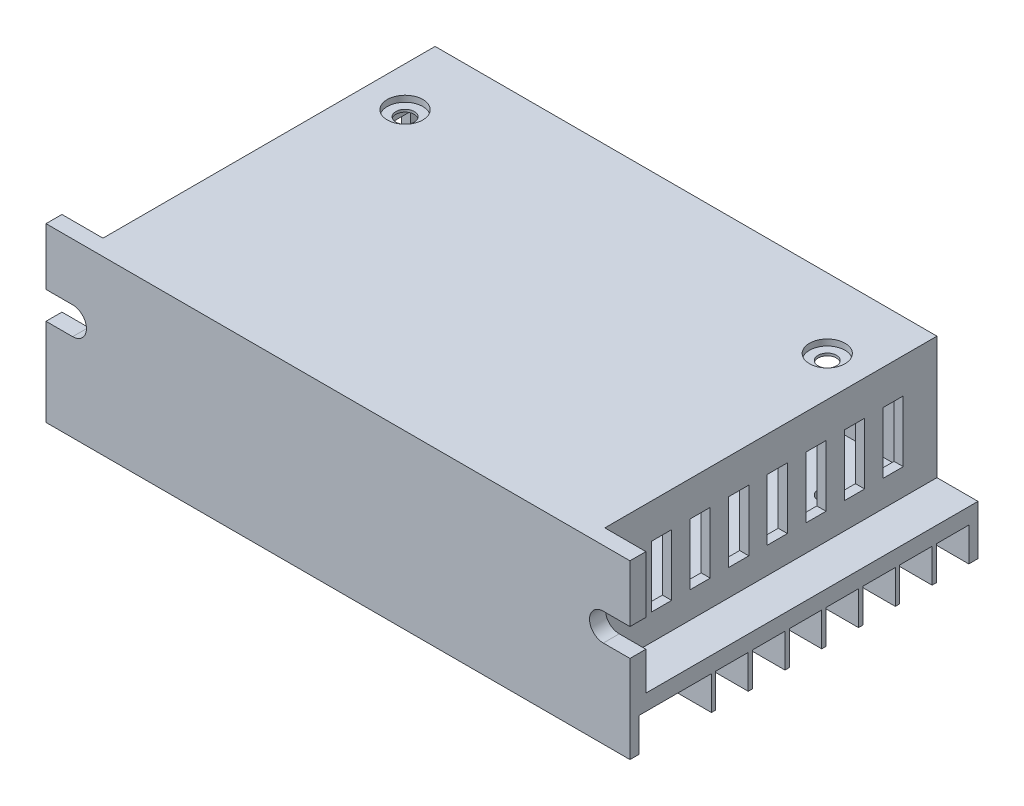
SolidWorks part; units mm, degrees
ref_plane "Front Plane" through (0, 0, 0) normal (0, 0, 1) x (1, 0, 0)
ref_plane "Top Plane" through (0, 0, 0) normal (0, 1, 0) x (1, 0, 0)
ref_plane "Right Plane" through (0, 0, 0) normal (1, 0, 0) x (0, 0, -1)
sketch "Sketch1" plane through (0, 0, 0) normal (0, 1, 0) x (1, 0, 0)
  line L1 (-47.65, 28.4) -> (47.65, 28.4)
  line L2 (-47.65, 28.4) -> (-47.65, -28.4)
  line L3 (-47.65, -28.4) -> (47.65, -28.4)
  line L4 (47.65, 28.4) -> (47.65, -28.4)
  line L5 (-47.65, 28.4) -> (47.65, -28.4) construction
  line L6 (-47.65, -28.4) -> (47.65, 28.4) construction
  point P0 (0, 0)
  dimension "D1" = 95.3
  dimension "D2" = 56.8
extrude "Boss-Extrude1" add sketch "Sketch1" along normal blind 28.1
sketch "Sketch2" plane through (-47.65, 0, 0) normal (-1, 0, 0) x (0, 0, 1)
  line L0 (-26.9, 0) -> (-26.9, 5.5)
  line L1 (-28.4, 0) -> (28.4, 0) construction
  line L2 (-26.9, 5.5) -> (-28.4, 5.5)
  line L3 (-28.4, 28.1) -> (-28.4, 0) construction
  line L4 (-28.4, 5.5) -> (-28.4, 0)
  line L5 (-28.4, 0) -> (-26.9, 0)
  line L6 (-15.6, 5.5) -> (-14.9, 5.5)
  line L7 (-21.6, 5.5) -> (-20.9, 5.5)
  line L8 (-21.6, 5.5) -> (-21.6, 0)
  line L9 (-21.6, 0) -> (-20.9, 0)
  line L10 (-20.9, 5.5) -> (-20.9, 0)
  line L11 (-15.6, 5.5) -> (-15.6, 0)
  line L12 (-14.9, 5.5) -> (-14.9, 0)
  line L13 (-15.6, 0) -> (-14.9, 0)
  line L14 (-9.6, 5.5) -> (-8.9, 5.5)
  line L15 (-9.6, 5.5) -> (-9.6, 0)
  line L16 (-8.9, 5.5) -> (-8.9, 0)
  line L17 (-9.6, 0) -> (-8.9, 0)
  line L18 (-3.6, 5.5) -> (-2.9, 5.5)
  line L19 (-3.6, 5.5) -> (-3.6, 0)
  line L20 (-2.9, 5.5) -> (-2.9, 0)
  line L21 (-3.6, 0) -> (-2.9, 0)
  line L22 (2.4, 5.5) -> (3.1, 5.5)
  line L23 (2.4, 5.5) -> (2.4, 0)
  line L24 (3.1, 5.5) -> (3.1, 0)
  line L25 (2.4, 0) -> (3.1, 0)
  line L26 (8.4, 5.5) -> (9.1, 5.5)
  line L27 (8.4, 5.5) -> (8.4, 0)
  line L28 (9.1, 5.5) -> (9.1, 0)
  line L29 (8.4, 0) -> (9.1, 0)
  line L30 (14.4, 5.5) -> (15.1, 5.5)
  line L31 (14.4, 5.5) -> (14.4, 0)
  line L32 (15.1, 5.5) -> (15.1, 0)
  line L33 (14.4, 0) -> (15.1, 0)
  line L35 (28.4, 0) -> (26.9, 0)
  line L36 (28.4, 0) -> (28.4, 5.5)
  line L37 (28.4, 5.5) -> (26.9, 5.5)
  line L38 (26.9, 0) -> (26.9, 5.5)
  line L39 (-28.4, 5.5) -> (28.4, 5.5)
  line L40 (-28.4, 5.5) -> (-28.4, 0)
  line L41 (-28.4, 0) -> (28.4, 0)
  line L42 (28.4, 5.5) -> (28.4, 0)
  line M25 (-28.4, 0) -> (28.4, 0)
  dimension "D1" = 1.5
  dimension "D2" = 5.5
  dimension "D3" = 0.7
  dimension "D4" = 5.3
  dimension "D5" = 7
extrude "Cut-Extrude2" cut sketch "Sketch2" against normal through all contours L39 L0 L8 M25 | L39 L10 L11 M25 | L39 L12 L15 M25 | L39 L16 L19 M25 | L39 L20 L23 M25 | L39 L24 L27 M25 | L39 L28 L31 M25 | L39 L32 L38 M25
sketch "Sketch3" plane through (0, 0, -28.4) normal (0, 0, -1) x (-1, 0, 0)
  line L0 (-47.65, 28.1) -> (47.65, 28.1) construction
  line L1 (-40.95, 28.1) -> (40.95, 28.1)
  line L2 (-40.95, 28.1) -> (-40.95, 8.1)
  line L3 (-40.95, 8.1) -> (40.95, 8.1)
  line L4 (40.95, 28.1) -> (40.95, 8.1)
  line L5 (-47.65, 0) -> (47.65, 0) construction
  line L6 (47.65, 28.1) -> (47.65, 0) construction
  line L7 (-47.65, 28.1) -> (47.65, 28.1)
  line L8 (-47.65, 28.1) -> (-47.65, 8.1)
  line L9 (-47.65, 8.1) -> (47.65, 8.1)
  line L10 (47.65, 28.1) -> (47.65, 8.1)
  point P9 (0, 8.1)
  line M10 (47.65, 0) -> (47.65, 28.1)
  line M11 (47.65, 28.1) -> (-47.65, 28.1)
  line M12 (-47.65, 28.1) -> (-47.65, 0)
  dimension "D1" = 81.9
  dimension "D2" = 8.1
extrude "Cut-Extrude4" cut sketch "Sketch3" against normal offset from surface (54.2 mm away) 2.6 contours L9 L2 M12 M11 | L4 L9 M10 M11 up to face at (0, 14.05, 28.4)
sketch "Sketch4" plane through (0, 0, 28.4) normal (0, 0, 1) x (1, 0, 0)
  line L0 (43.3, 16.55) -> (52, 16.55) construction
  line L1 (43.3, 18.8) -> (52, 18.8)
  line L2 (43.3, 14.3) -> (52, 14.3)
  line L3 (47.65, 28.1) -> (47.65, 0) construction
  line L4 (-47.65, 28.1) -> (47.65, 28.1) construction
  arc A0 (43.3, 18.8) -> (43.3, 14.3) centre (43.3, 16.55) ccw
  arc A1 (52, 14.3) -> (52, 18.8) centre (52, 16.55) ccw
  point P2 (47.65, 16.55)
  dimension "D2" = 4.35
  dimension "D1" = 4.5
  dimension "D3" = 9.3
extrude "Cut-Extrude5" cut sketch "Sketch4" against normal through all
mirror "Mirror1" about plane through (0, 0, 0) normal (1, 0, 0) of "Cut-Extrude5"
sketch "Sketch5" plane through (40.95, 0, 0) normal (1, 0, 0) x (0, 0, -1)
  line L0 (-25.8, 28.1) -> (28.4, 28.1) construction
  line L1 (-18.2, 22.4) -> (-14.9, 22.4)
  line L2 (-18.2, 22.4) -> (-18.2, 12.4)
  line L3 (-18.2, 12.4) -> (-14.9, 12.4)
  line L4 (-14.9, 22.4) -> (-14.9, 12.4)
  line L5 (-28.4, 14.3) -> (-28.4, 0) construction
  line L6 (-11.9, 22.4) -> (-8.6, 22.4)
  line L7 (-11.9, 22.4) -> (-11.9, 12.4)
  line L8 (-11.9, 12.4) -> (-8.6, 12.4)
  line L9 (-8.6, 22.4) -> (-8.6, 12.4)
  line L10 (-5.6, 22.4) -> (-2.3, 22.4)
  line L11 (-5.6, 22.4) -> (-5.6, 12.4)
  line L12 (-5.6, 12.4) -> (-2.3, 12.4)
  line L13 (-2.3, 22.4) -> (-2.3, 12.4)
  line L14 (0.7, 22.4) -> (4, 22.4)
  line L15 (0.7, 22.4) -> (0.7, 12.4)
  line L16 (0.7, 12.4) -> (4, 12.4)
  line L17 (4, 22.4) -> (4, 12.4)
  line L18 (7, 22.4) -> (10.3, 22.4)
  line L19 (7, 22.4) -> (7, 12.4)
  line L20 (7, 12.4) -> (10.3, 12.4)
  line L21 (10.3, 22.4) -> (10.3, 12.4)
  line L22 (13.3, 22.4) -> (16.6, 22.4)
  line L23 (13.3, 22.4) -> (13.3, 12.4)
  line L24 (13.3, 12.4) -> (16.6, 12.4)
  line L25 (16.6, 22.4) -> (16.6, 12.4)
  line L26 (19.6, 22.4) -> (22.9, 22.4)
  line L27 (19.6, 22.4) -> (19.6, 12.4)
  line L28 (19.6, 12.4) -> (22.9, 12.4)
  line L29 (22.9, 22.4) -> (22.9, 12.4)
  dimension "D1" = 10
  dimension "D2" = 5.7
  dimension "D3" = 3.3
  dimension "D4" = 10.2
  dimension "D5" = 7
extrude "Cut-Extrude6" cut sketch "Sketch5" against normal through all
sketch "Sketch6" plane through (0, 28.1, 0) normal (0, 1, 0) x (1, 0, 0)
  line L8 (-39.45, -25.8) -> (39.45, -25.8)
  line L9 (-40.95, -25.8) -> (-47.65, -25.8) construction
  line L16 (39.45, -26.9) -> (39.45, 26.9)
  line L17 (39.45, 26.9) -> (-39.45, 26.9)
  line L18 (-39.45, 26.9) -> (-39.45, -26.9)
  line L19 (-39.45, -26.9) -> (39.45, -26.9)
  line L20 (39.45, -25.8) -> (39.45, 26.9)
  line L21 (39.45, 26.9) -> (-39.45, 26.9)
  line L22 (-39.45, 26.9) -> (-39.45, -25.8)
  dimension "D1" = 1.5
extrude "Cut-Extrude8" cut sketch "Sketch6" against normal up to surface (18.6 mm away) from offset 1.4 up to face at (-44.3, 8.1, -1.3) offset against normal yes
sketch "Sketch7" plane through (-40.95, 0, 0) normal (-1, 0, 0) x (0, 0, 1)
  line L0 (-28.4, 28.1) -> (-28.4, 8.1) construction
  line L1 (-12.5, 25) -> (6.5, 25)
  line L2 (-12.5, 25) -> (-12.5, 14.5)
  line L3 (-12.5, 14.5) -> (6.5, 14.5)
  line L4 (6.5, 25) -> (6.5, 14.5)
  line L5 (25.8, 28.1) -> (-28.4, 28.1) construction
  line L6 (25.8, 8.1) -> (-28.4, 8.1) construction
  line L7 (25.8, 8.1) -> (25.8, 28.1) construction
  dimension "D1" = 15.9
  dimension "D2" = 3.1
  dimension "D3" = 6.4
  dimension "D4" = 19.3
extrude "Cut-Extrude9" cut sketch "Sketch7" against normal up to next
sketch "Sketch8" plane through (0, 0, -28.4) normal (0, 0, -1) x (-1, 0, 0)
  line L0 (-40.95, 28.1) -> (40.95, 28.1) construction
  line L1 (-33.15, 24.3) -> (33.15, 24.3)
  line L2 (-33.15, 24.3) -> (-33.15, 13.5)
  line L3 (-33.15, 13.5) -> (33.15, 13.5)
  line L4 (33.15, 24.3) -> (33.15, 13.5)
  point P4 (0, 24.3)
  dimension "D1" = 66.3
  dimension "D2" = 10.8
  dimension "D3" = 3.8
extrude "Cut-Extrude10" cut sketch "Sketch8" against normal up to next
sketch "Sketch9" plane through (0, 28.1, 0) normal (0, 1, 0) x (1, 0, 0)
  line L0 (-40.95, -25.8) -> (-40.95, 28.4) construction
  line L1 (40.95, 28.4) -> (-40.95, 28.4) construction
  point P0 (-34.45, 17)
  dimension "D1" = 6.5
  dimension "D2" = 11.4
hole_wizard "CBORE for M5 Hex Head Bolt1" positions "Sketch9" profile "Sketch10" counterbore size "M5" standard "ANSI Metric" end condition through all
sketch "Sketch10" plane through (-34.45, 28.1, -17) normal (1, 0, 0) x (0, 0, 1)
  line L0 (0, 0) -> (0, 28.1)
  line L1 (0, 28.1) -> (1.5, 28.1)
  line L3 (1.5, 28.1) -> (1.5, 1)
  line L4 (1.5, 1) -> (2.9, 1)
  line L5 (2.9, 1) -> (2.9, 0)
  line L7 (2.9, 0) -> (0, 0)
  line L11 (0, -6.35) -> (0, 107.95) construction
  dimension "Thru Hole Dia." = 3
  dimension "Thru Hole Depth" = 28.1
  dimension "C'Bore Dia." = 5.8
  dimension "C'Bore Depth" = 1
mirror "Mirror2" about plane through (0, 0, 0) normal (1, 0, 0) of "CBORE for M5 Hex Head Bolt1"
equation "\"mDriverWidth\" = 56.8"
equation "\"mDriverLength\" =95.3"
equation "\"mDriverHeight\" = 28.1"
equation "\"D1@Boss-Extrude1\"=\"mDriverHeight\""
equation "\"D2@Sketch1\"=\"mDriverWidth\""
equation "\"D1@Sketch1\"=\"mDriverLength\""
